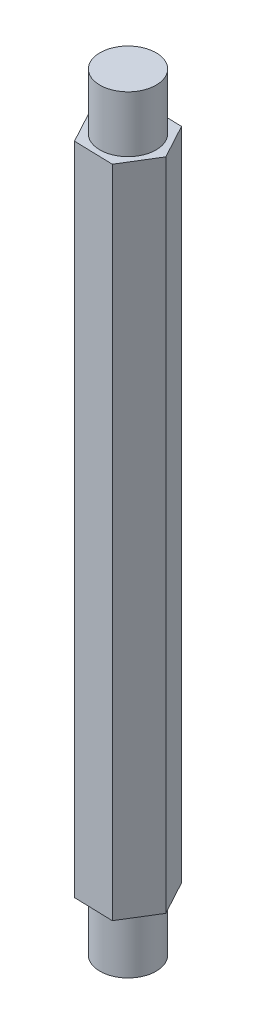
SolidWorks part; units mm, degrees
material "Brass"
ref_plane "Front Plane" through (0, 0, 0) normal (0, 0, 1) x (1, 0, 0)
ref_plane "Top Plane" through (0, 0, 0) normal (0, 1, 0) x (1, 0, 0)
ref_plane "Right Plane" through (0, 0, 0) normal (1, 0, 0) x (0, 0, -1)
sketch "Sketch1" plane through (0, 0, 0) normal (0, 1, 0) x (1, 0, 0)
  circle A0 centre (0, 0) radius 1.5
  dimension "D1" = 3
extrude "Boss-Extrude1" add sketch "Sketch1" along normal blind 3
sketch "Sketch2" plane through (0, 3, 0) normal (0, 1, 0) x (1, 0, 0)
  line L0 (0, 0) -> (-1.5, 0) construction
  line L1 (-0.9892, 1.828) -> (-2.0777, 0.0574)
  line L2 (-2.0777, 0.0574) -> (-1.0885, -1.7706)
  line L3 (-1.0885, -1.7706) -> (0.9892, -1.828)
  line L4 (0.9892, -1.828) -> (2.0777, -0.0574)
  line L5 (2.0777, -0.0574) -> (1.0885, 1.7706)
  line L6 (1.0885, 1.7706) -> (-0.9892, 1.828)
  circle A0 centre (0, 0) radius 1.8 construction
  circle A1 centre (0, 0) radius 1.5 construction
  dimension "D2" = 178.418
  dimension "D1" = 1.8
extrude "Boss-Extrude2" add sketch "Sketch2" along normal blind 35
sketch "Sketch3" plane through (0, 38, 0) normal (0, 1, 0) x (1, 0, 0)
  circle A0 centre (0, 0) radius 1.5
  dimension "D1" = 3
extrude "Boss-Extrude3" add sketch "Sketch3" along normal blind 3
